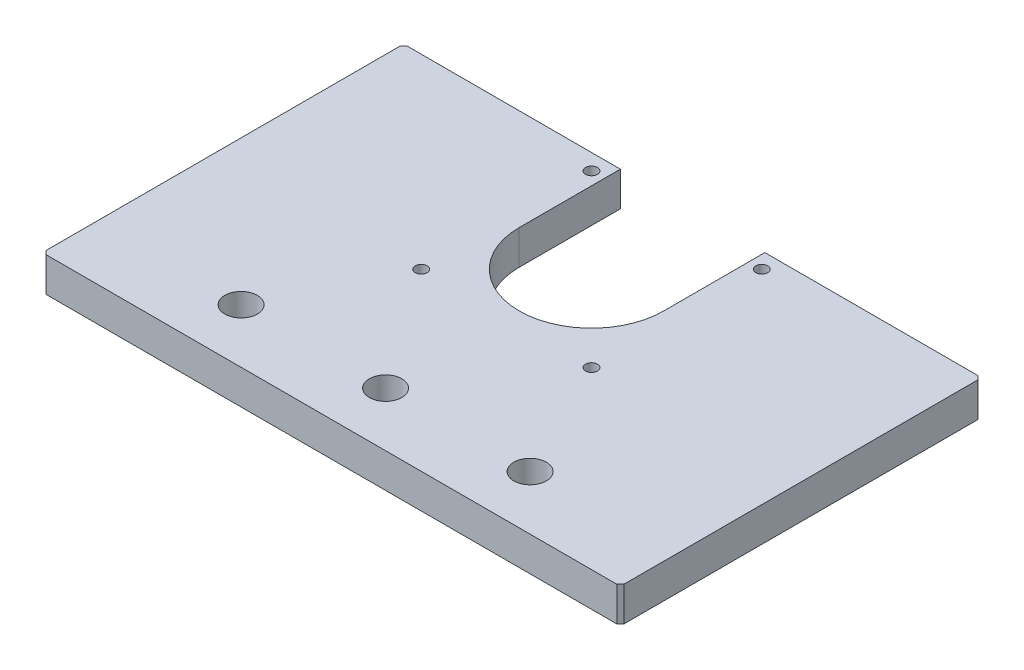
SolidWorks part; units mm, degrees
material "6061-T6 (SS)"
ref_plane "Front Plane" through (0, 0, 0) normal (0, 0, 1) x (1, 0, 0)
ref_plane "Top Plane" through (0, 0, 0) normal (0, 1, 0) x (1, 0, 0)
ref_plane "Right Plane" through (0, 0, 0) normal (1, 0, 0) x (0, 0, -1)
sketch "Sketch1" plane through (0, 0, 0) normal (0, 1, 0) x (1, 0, 0)
  line L0 (20, 0) -> (20, 28)
  line L1 (20, 28) -> (80, 28)
  line L2 (80, 28) -> (80, -72)
  line L3 (80, -72) -> (-80, -72)
  line L4 (-80, -72) -> (-80, 28)
  line L5 (-80, 28) -> (-20, 28)
  line L6 (-20, 28) -> (-20, 0)
  line L7 (-125.0932, -37) -> (-101.7391, -37) construction
  line L8 (-40, -57) -> (0, -57) construction
  line L9 (0, -57) -> (40, -57) construction
  line L10 (0, -55) -> (0, 55) construction
  line L12 (23.5732, 23.5732) -> (-23.5732, 23.5732) construction
  line L13 (23.5732, 23.5732) -> (23.5732, -23.5732) construction
  line L14 (23.5732, -23.5732) -> (-23.5732, -23.5732) construction
  line L15 (-23.5732, 23.5732) -> (-23.5732, -23.5732) construction
  line L16 (23.5732, 23.5732) -> (-23.5732, -23.5732) construction
  line L17 (23.5732, -23.5732) -> (-23.5732, 23.5732) construction
  arc A0 (-20, 0) -> (20, 0) centre (0, 0) ccw
  circle A1 centre (0, 0) radius 33.3375 construction
  dimension "D1" = 20
  dimension "D7" = 66.675
  dimension "D2" = 37
  dimension "D3" = 40
  dimension "D4" = 20
  dimension "D5" = 100
  dimension "D6" = 65
  dimension "D8" = 15
  dimension "D9" = 160
extrude "Boss-Extrude1" add sketch "Sketch1" along normal mid plane 9.525
hole_wizard "M8 Clearance Hole1" positions "Sketch2" profile "Sketch3" hole size "M8" standard "ANSI Metric" end condition through all
sketch "Sketch2" plane through (0, 4.7625, 0) normal (0, 1, 0) x (1, 0, 0)
  point P0 (-40, -57)
  point P3 (0, -57)
  point P6 (40, -57)
sketch "Sketch3" plane through (-40, 4.7625, 57) normal (1, 0, 0) x (0, 0, 1)
  line L0 (0, 0) -> (0, 9.525)
  line L1 (0, 9.525) -> (4.5, 9.525)
  line L2 (4.5, 9.525) -> (4.5, 0)
  line L5 (4.5, 0) -> (0, 0)
  line L11 (0, -6.35) -> (0, 107.95) construction
  dimension "Thru Hole Dia." = 9
  dimension "Thru Hole Depth" = 9.525
hole_wizard "M4x0.7 Tapped Hole2" positions "Sketch4" profile "Sketch5" tap size "M4x0.7" standard "ANSI Metric" end condition up to next
sketch "Sketch4" plane through (0, 4.7625, 0) normal (0, 1, 0) x (1, 0, 0)
  point P0 (-23.5732, -23.5732)
  point P3 (-23.5732, 23.5732)
  point P6 (23.5732, 23.5732)
  point P9 (23.5732, -23.5732)
sketch "Sketch5" plane through (-23.5732, 4.7625, 23.5732) normal (1, 0, 0) x (0, 0, 1)
  line L0 (0, 0) -> (0, 9.525)
  line L1 (0, 9.525) -> (1.65, 9.525)
  line L2 (1.65, 9.525) -> (1.65, 0)
  line L5 (1.65, 0) -> (0, 0)
  line L11 (0, -6.35) -> (0, 107.95) construction
  dimension "Thru Tap Drill Dia." = 3.3
  dimension "Thru Tap Drill Depth" = 9.525
cosmetic thread "Hole Thread1"
cosmetic thread "Hole Thread2"
cosmetic thread "Hole Thread3"
cosmetic thread "Hole Thread4"
chamfer "Chamfer1" distance 1 4 edges at (-80, 0, -28) (-80, 0, 72) (80, 0, 72) (80, 0, -28)
